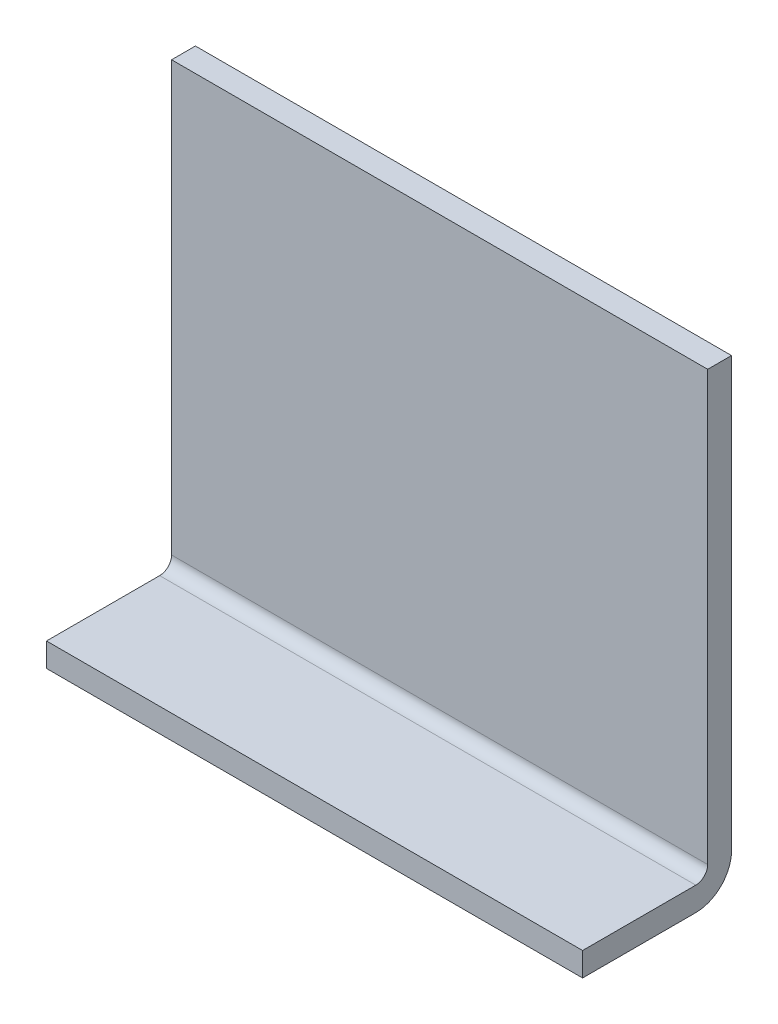
SolidWorks part; units mm, degrees
ref_plane "Front Plane" through (0, 0, 0) normal (0, 0, 1) x (1, 0, 0)
ref_plane "Top Plane" through (0, 0, 0) normal (0, 1, 0) x (1, 0, 0)
ref_plane "Right Plane" through (0, 0, 0) normal (1, 0, 0) x (0, 0, -1)
sketch "Sketch1" plane through (0, 0, 0) normal (0, 1, 0) x (1, 0, 0)
  line L1 (0, 0) -> (45, 0)
  line L2 (0, 0) -> (0, 12.5)
  line L3 (0, 12.5) -> (45, 12.5)
  line L4 (45, 0) -> (45, 12.5)
  dimension "D1" = 12.5
  dimension "D2" = 45
extrude "Boss-Extrude1" add sketch "Sketch1" along normal blind 2
sketch "Sketch2" plane through (0, 0, -12.5) normal (0, 0, -1) x (-1, 0, 0)
  line L1 (-45, 2) -> (0, 2)
  line L2 (-45, 2) -> (-45, 39)
  line L3 (-45, 39) -> (0, 39)
  line L4 (0, 2) -> (0, 39)
  dimension "D1" = 37
extrude "Boss-Extrude2" add sketch "Sketch2" against normal blind 2
fillet "Fillet1" radius 1 1 edges at (22.5, 2, -10.5)
fillet "Fillet2" radius 3 1 edges at (22.5, 0, -12.5)
